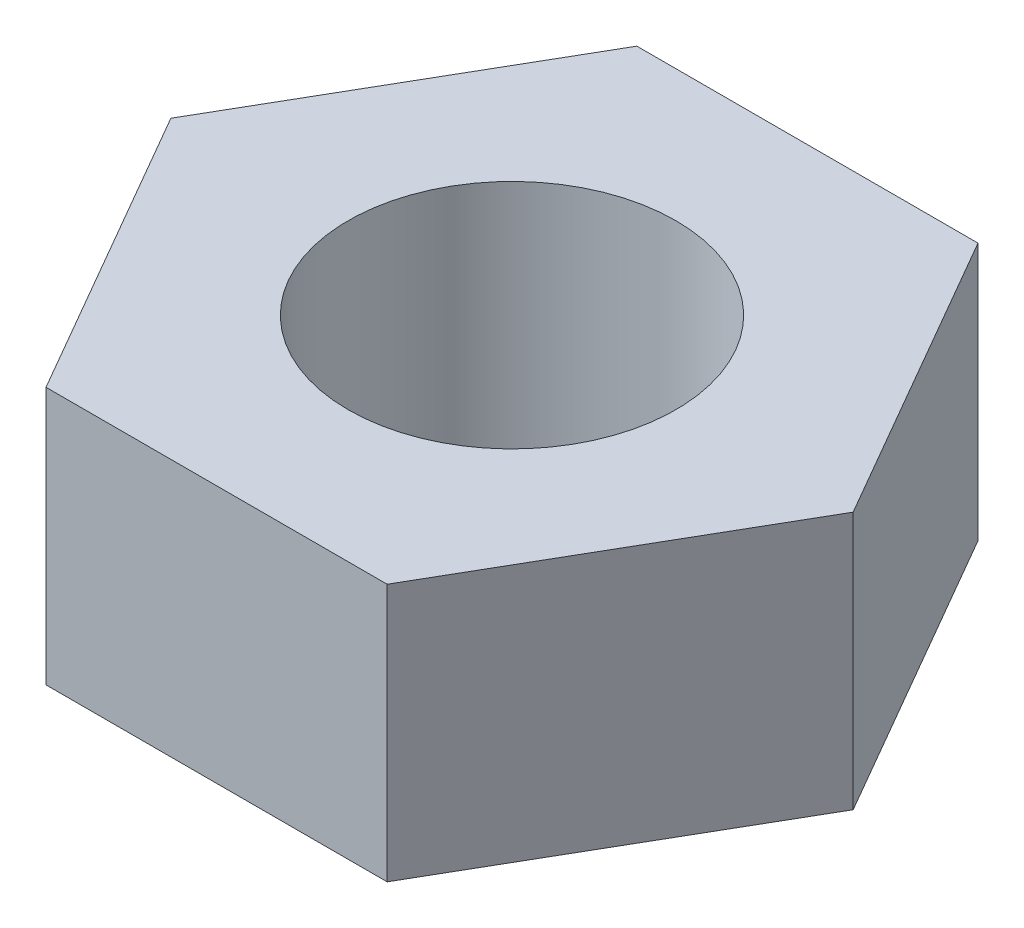
SolidWorks part; units mm, degrees
ref_plane "Front Plane" through (0, 0, 0) normal (0, 0, 1) x (1, 0, 0)
ref_plane "Top Plane" through (0, 0, 0) normal (0, 1, 0) x (1, 0, 0)
ref_plane "Right Plane" through (0, 0, 0) normal (1, 0, 0) x (0, 0, -1)
sketch "Sketch1" plane through (0, 0, 0) normal (0, 1, 0) x (1, 0, 0)
  line L1 (3.1235, 0) -> (1.5617, 2.705)
  line L2 (1.5617, 2.705) -> (-1.5617, 2.705)
  line L3 (-1.5617, 2.705) -> (-3.1235, 0)
  line L4 (-3.1235, 0) -> (-1.5617, -2.705)
  line L5 (-1.5617, -2.705) -> (1.5617, -2.705)
  line L6 (1.5617, -2.705) -> (3.1235, 0)
  circle A0 centre (0, 0) radius 2.705 construction
  circle A1 centre (0, 0) radius 1.5
  dimension "D2" = 3
  dimension "D1" = 5.41
extrude "Boss-Extrude1" add sketch "Sketch1" along normal blind 2.36
